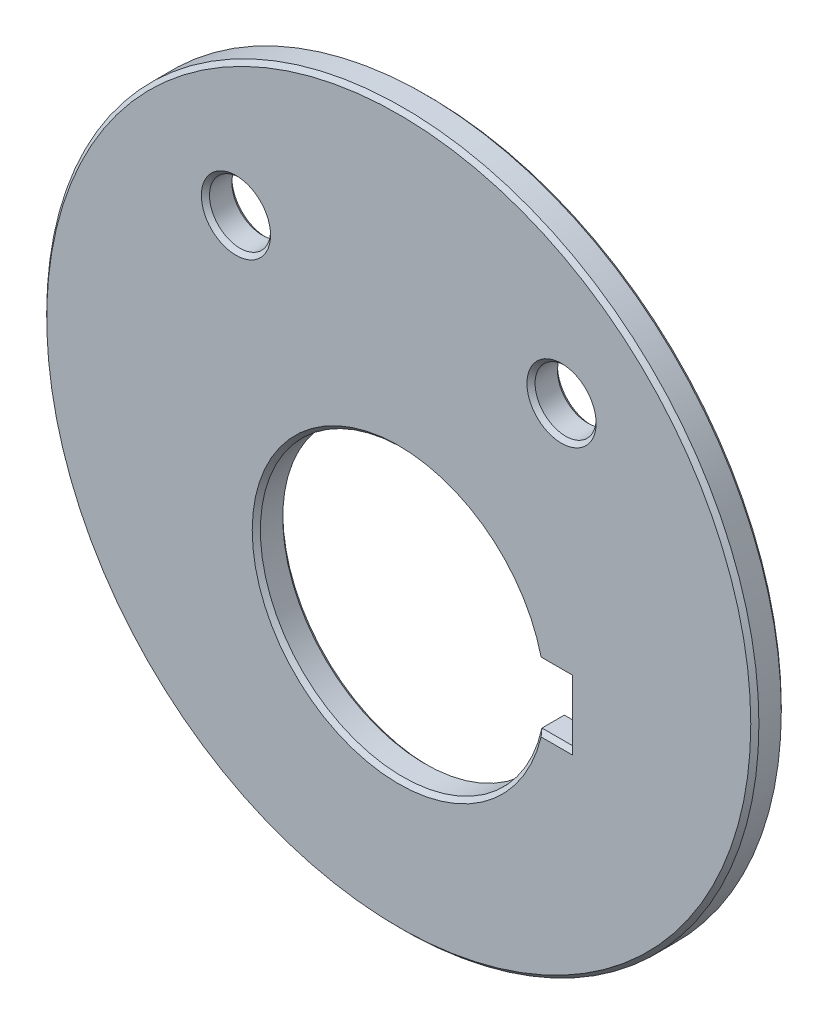
SolidWorks part; units mm, degrees
ref_plane "Front Plane" through (0, 0, 0) normal (0, 0, 1) x (1, 0, 0)
ref_plane "Top Plane" through (0, 0, 0) normal (0, 1, 0) x (1, 0, 0)
ref_plane "Right Plane" through (0, 0, 0) normal (1, 0, 0) x (0, 0, -1)
sketch "Sketch1" plane through (0, 0, 0) normal (0, 0, 1) x (1, 0, 0)
  line L1 (8.3374, -2.5) -> (6.8374, -2.5)
  line L2 (8.3374, -2.5) -> (8.3374, -5.5)
  line L3 (8.3374, -5.5) -> (6.8374, -5.5)
  circle A0 centre (0, 0) radius 17.5
  arc A1 (6.8374, -2.5) -> (6.8374, -5.5) centre (0, -4) ccw
  circle A2 centre (-8, 9) radius 1.5
  circle A3 centre (8, 9) radius 1.5
  point P4 (8.3374, -4)
  dimension "D1" = 35
  dimension "D2" = 14
  dimension "D10" = 3
  dimension "D11" = 3
  dimension "D3" = 4
  dimension "D4" = 1.5
  dimension "D5" = 3
  dimension "D6" = 8
  dimension "D7" = 8
  dimension "D8" = 9
  dimension "D9" = 9
extrude "Boss-Extrude1" add sketch "Sketch1" along normal blind 1.5
chamfer "Chamfer1" distance 0.2 angle 45 14 edges at (-6.5, 9, 0) (9.5, 9, 0) (7.5874, -5.5, 0) (-7, -4, 0) (7.5874, -2.5, 0) (8.3374, -4, 0) (17.5, 0, 0) (-6.5, 9, 1.5) (-7, -4, 1.5) (7.5874, -5.5, 1.5) (8.3374, -4, 1.5) (7.5874, -2.5, 1.5) (17.5, 0, 1.5) (9.5, 9, 1.5)
